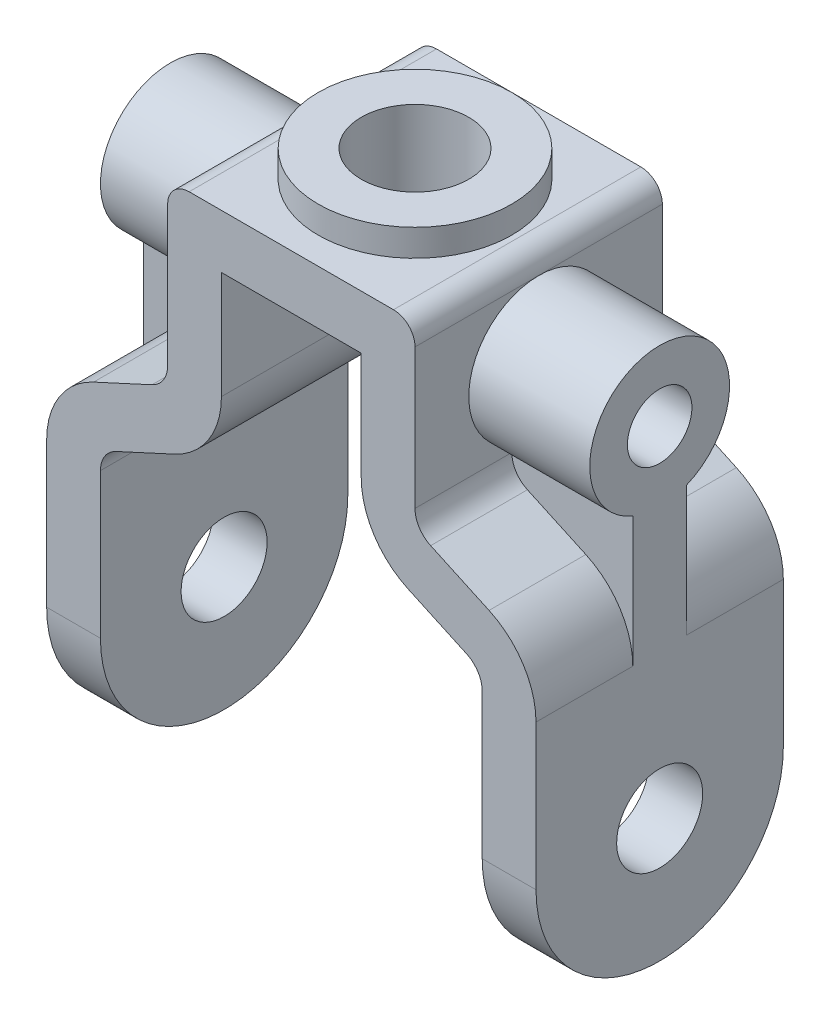
SolidWorks part; units mm, degrees
ref_plane "Front Plane" through (0, 0, 0) normal (0, 0, 1) x (1, 0, 0)
ref_plane "Top Plane" through (0, 0, 0) normal (0, 1, 0) x (1, 0, 0)
ref_plane "Right Plane" through (0, 0, 0) normal (1, 0, 0) x (0, 0, -1)
sketch "Sketch1" plane through (0, 0, 0) normal (0, 0, 1) x (1, 0, 0)
  line L0 (0, 0) -> (13, 0)
  line L1 (13, 0) -> (13, -20)
  line L2 (21.7281, -33.6258) -> (32.5906, -38.6258)
  line L3 (35.5, -43.1678) -> (35.5, -93.1678)
  line L4 (-19, 10) -> (19, 10)
  line L5 (23, 6) -> (23, -20)
  line L6 (25.9094, -24.5419) -> (36.7719, -29.5419)
  line L7 (45.5, -43.1678) -> (45.5, -93.1678)
  line L8 (0, 10) -> (23, 10) construction
  line L9 (23, 10) -> (23, -20) construction
  line L10 (35.5, -93.1678) -> (45.5, -93.1678)
  line L11 (0, 0) -> (0, -27.0419) construction
  line L12 (-35.5, -93.1678) -> (-45.5, -93.1678)
  line L13 (-45.5, -43.1678) -> (-45.5, -93.1678)
  line L14 (-25.9094, -24.5419) -> (-36.7719, -29.5419)
  line L15 (-23, 6) -> (-23, -20)
  line L16 (-35.5, -43.1678) -> (-35.5, -93.1678)
  line L17 (-21.7281, -33.6258) -> (-32.5906, -38.6258)
  line L18 (0, 0) -> (-13, 0)
  line L19 (-13, 0) -> (-13, -20)
  arc A0 (13, -20) -> (21.7281, -33.6258) centre (28, -20) ccw
  arc A1 (35.5, -43.1678) -> (32.5906, -38.6258) centre (30.5, -43.1678) ccw
  arc A2 (23, -20) -> (25.9094, -24.5419) centre (28, -20) ccw
  arc A3 (45.5, -43.1678) -> (36.7719, -29.5419) centre (30.5, -43.1678) ccw
  arc A4 (23, 6) -> (19, 10) centre (19, 6) ccw
  arc A5 (-23, 6) -> (-19, 10) centre (-19, 6) cw
  arc A6 (-45.5, -43.1678) -> (-36.7719, -29.5419) centre (-30.5, -43.1678) cw
  arc A7 (-23, -20) -> (-25.9094, -24.5419) centre (-28, -20) cw
  arc A8 (-35.5, -43.1678) -> (-32.5906, -38.6258) centre (-30.5, -43.1678) cw
  arc A9 (-13, -20) -> (-21.7281, -33.6258) centre (-28, -20) cw
  dimension "D3" = 30
  dimension "D4" = 10
  dimension "D10" = 8
  dimension "D1" = 13
  dimension "D2" = 20
  dimension "D5" = 50
  dimension "D6" = 22.5
  dimension "D7" = 11.9581
  dimension "D8" = 5
  dimension "D9" = 10
extrude "Boss-Extrude1" add sketch "Sketch1" along normal mid plane 46
sketch "Sketch2" plane through (45.5, 0, 0) normal (1, 0, 0) x (0, 0, -1)
  line L0 (-23, -93.1678) -> (23, -93.1678) construction
  line L1 (0, -70.1678) -> (23, -93.1678) construction
  line L3 (-23, -70.1678) -> (-23, -93.1678)
  line L4 (-23, -93.1678) -> (23, -93.1678)
  line L5 (23, -70.1678) -> (23, -93.1678)
  line L7 (-23, -93.1678) -> (0, -70.1678) construction
  arc A0 (-23, -70.1678) -> (23, -70.1678) centre (0, -70.1678) ccw
  circle A1 centre (0, -70.1678) radius 8
  line M1 (23, -93.1678) -> (23, -43.1678)
  line M3 (-23, -43.1678) -> (-23, -93.1678)
  line M4 (-23, -93.1678) -> (23, -93.1678)
  dimension "D1" = 46
  dimension "D2" = 16
extrude "Cut-Extrude1" cut sketch "Sketch2" against normal through all contours A1 | A0 M3 M4 | A0 L4 M1
sketch "Sketch3" plane through (0, 10, 0) normal (0, 1, 0) x (1, 0, 0)
  circle A0 centre (0, 0) radius 18
  circle A1 centre (0, 0) radius 10
  dimension "D1" = 20
  dimension "D2" = 36
extrude "Boss-Extrude2" add sketch "Sketch3" along normal blind 5
sketch "Sketch4" plane through (0, 10, 0) normal (0, 1, 0) x (1, 0, 0)
  circle A0 centre (0, 0) radius 10
extrude "Cut-Extrude2" cut sketch "Sketch4" against normal up to next
sketch "Sketch5" plane through (45.5, 0, 0) normal (1, 0, 0) x (0, 0, -1)
  line L1 (5, -60.3793) -> (5, -19)
  line L2 (-5, -60.3793) -> (-5, -19)
  line L4 (-23, 6) -> (23, 6) construction
  line L5 (-5, -60.3793) -> (5, -60.3793)
  circle A0 centre (0, -7) radius 6
  arc A1 (5, -19) -> (-5, -19) centre (0, -7) ccw
  dimension "D2" = 12
  dimension "D1" = 26
extrude "Boss-Extrude3" add sketch "Sketch5" against normal up to next
sketch "Sketch7" plane through (23, 0, 0) normal (1, 0, 0) x (0, 0, -1)
  circle A0 centre (0, -7) radius 6
extrude "Cut-Extrude4" cut sketch "Sketch7" against normal up to next
mirror "Mirror1" about plane through (0, 0, 0) normal (1, 0, 0) of "Cut-Extrude4", "Boss-Extrude3"
